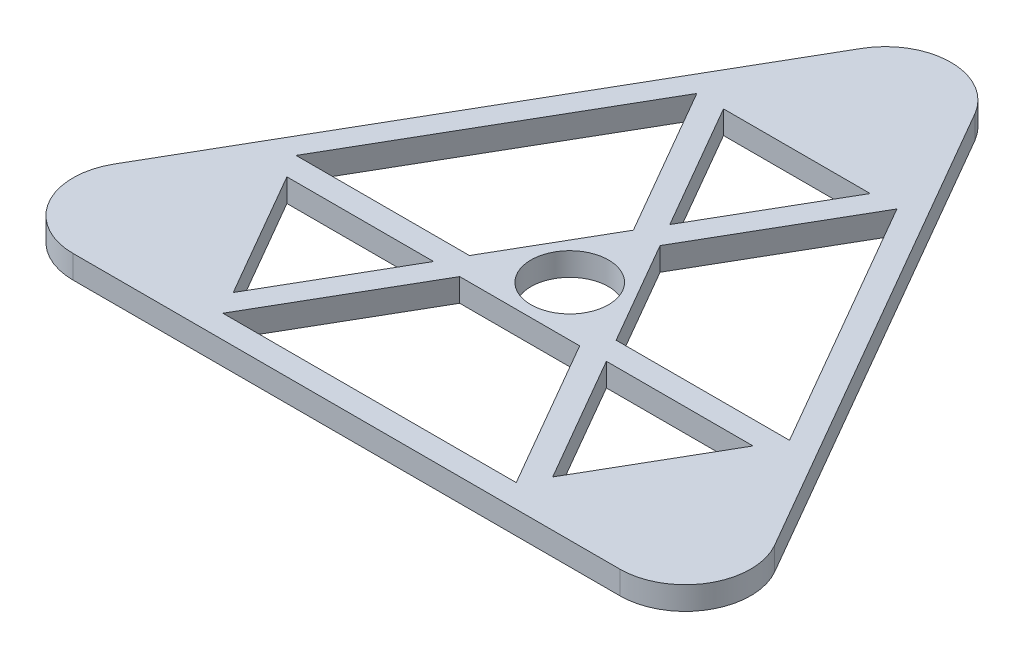
SolidWorks part; units mm, degrees
ref_plane "前视基准面" through (0, 0, 0) normal (0, 0, 1) x (1, 0, 0)
ref_plane "上视基准面" through (0, 0, 0) normal (0, 1, 0) x (1, 0, 0)
ref_plane "右视基准面" through (0, 0, 0) normal (1, 0, 0) x (0, 0, -1)
other "Configuration Table"
sketch "草图2" plane through (0, 0, 0) normal (0, 1, 0) x (1, 0, 0)
  line L6 (8.6547, 19.6506) -> (8.9307, 19.1726)
  line L7 (-22.5, -4.3301) -> (-15, -17.3205)
  line L8 (-15, 8.6603) -> (43286.2702, -24991.3397) construction
  line L9 (0, 34.641) -> (0, -49965.359) construction
  line L10 (22.5, -4.3301) -> (15, -17.3205)
  line L11 (-7.5, 21.6506) -> (7.5, 21.6506)
  line L17 (-6.3453, 19.6506) -> (6.3453, 19.6506)
  line L18 (-19.2807, -17.3205) -> (-19.3357, -17.3205)
  line L20 (12.6906, -17.3205) -> (-12.6906, -17.3205)
  line L22 (-22.5, -4.3301) -> (-21.3453, -2.3301)
  line L23 (6.3453, 19.6506) -> (0, 8.6603)
  line L25 (20.1906, -4.3301) -> (13.8453, -15.3205)
  line L26 (-13.7928, -15.3205) -> (-20.1381, -4.3301)
  line L28 (6.3453, 19.6506) -> (0, 8.6603)
  line L29 (-21.3453, -2.3301) -> (-6.3453, -2.3301)
  line L30 (-12.6906, -17.3205) -> (-5.1906, -4.3301)
  line L31 (12.6906, -17.3205) -> (5.1906, -4.3301)
  line L32 (21.3453, -2.3301) -> (6.3453, -2.3301)
  line L33 (8.6547, 19.6506) -> (1.1547, 6.6603)
  line L34 (-8.6547, 19.6506) -> (-1.1547, 6.6603)
  line L35 (-1.1547, 6.6603) -> (-6.3453, -2.3301)
  line L36 (-13.7928, -15.3205) -> (-7.4475, -4.3301)
  line L37 (0, 8.6603) -> (-6.3453, 19.6506)
  line L38 (1.1547, 6.6603) -> (6.3453, -2.3301)
  line L39 (13.8453, -15.3205) -> (7.5, -4.3301)
  line L40 (-20.1381, -4.3301) -> (-7.4475, -4.3301)
  line L41 (-5.1906, -4.3301) -> (5.1906, -4.3301)
  line L42 (7.5, -4.3301) -> (20.1906, -4.3301)
  line L43 (-28.6579, -10.9959) -> (-4.9047, 30.1458)
  line L44 (4.9047, 30.1458) -> (28.6579, -10.9959)
  line L45 (-7.5, 21.6506) -> (-5.3322, 25.4055)
  line L46 (23.6547, -19.3205) -> (-23.6547, -19.3205)
  line L47 (-8.6547, 19.6506) -> (-21.3453, -2.3301)
  line L48 (-22.5, -4.3301) -> (-24.6678, -8.0849)
  line L49 (-15, -17.3205) -> (-19.2807, -17.3205)
  line L50 (-12.6906, -17.3205) -> (12.6906, -17.3205)
  line L51 (15, -17.3205) -> (19.3357, -17.3205)
  line L52 (22.5, -4.3301) -> (24.6678, -8.0849)
  line L53 (8.9307, 19.1726) -> (21.3453, -2.3301)
  line L54 (7.5, 21.6506) -> (5.3322, 25.4055)
  circle A2 centre (-23.6547, -13.657) radius 5.6635
  circle A3 centre (23.6547, -13.657) radius 5.6635
  circle A4 centre (0, 27.3141) radius 5.6635
  dimension "D4" = 15
extrude "凸台-拉伸17" add sketch "草图2" along normal blind 2
ref_plane "基准面1" through (0, 2, 0) normal (0, 1, 0) x (1, 0, 0)
sketch "草图3" plane through (0, 2, 0) normal (0, 1, 0) x (1, 0, 0)
  line L0 (-4.9047, 30.1458) -> (-28.5594, -10.8253)
  line L1 (-28.5594, -10.8253) -> (-4.9047, 30.1458) construction
  line L2 (-23.6547, -19.3205) -> (23.6547, -19.3205)
  line L3 (4.9047, 30.1458) -> (28.5594, -10.8253)
  line L4 (4.9047, 30.1458) -> (28.5594, -10.8253) construction
  line L5 (-21.3453, -2.3301) -> (-12.6906, -17.3205)
  line L6 (-12.6906, -17.3205) -> (19.3357, -17.3205)
  line L7 (19.3357, -17.3205) -> (-19.3357, -17.3205)
  line L8 (-21.3453, -2.3301) -> (-5.2864, 25.2821)
  line L9 (-5.2864, 25.2821) -> (-24.6952, -8.09)
  line L10 (8.6547, 19.6506) -> (5.3322, 25.4055)
  line L11 (-8.6547, 21.6406) -> (8.6547, 21.6406)
  line L12 (5.3322, 25.4055) -> (24.6678, -8.0849)
  line L13 (-8.6547, 19.6506) -> (8.6547, 19.6506)
  line L14 (21.3453, -2.3301) -> (12.6906, -17.3205)
  line L16 (23.0687, -3.3251) -> (14.414, -18.3155)
  circle A0 centre (0, 0) radius 3.356
  circle A1 centre (-28.4325, -16.5764) radius 0.0644
  circle A2 centre (-23.6547, -13.657) radius 5.6635
  circle A3 centre (0, 27.3141) radius 5.6635
  circle A4 centre (23.6547, -13.657) radius 5.6635
  point P46 (0, 0)
  point P47 (-23.6547, -13.657)
  point P50 (-23.6547, -13.657)
  point P51 (0, 0)
  dimension "D3" = 1.99
  dimension "D1" = 1.99
sketch "草图4" plane through (0, 2, 0) normal (0, 1, 0) x (1, 0, 0)
  circle A0 centre (0, 0) radius 3.356
extrude "切除-拉伸25" cut sketch "草图4" against normal through all
